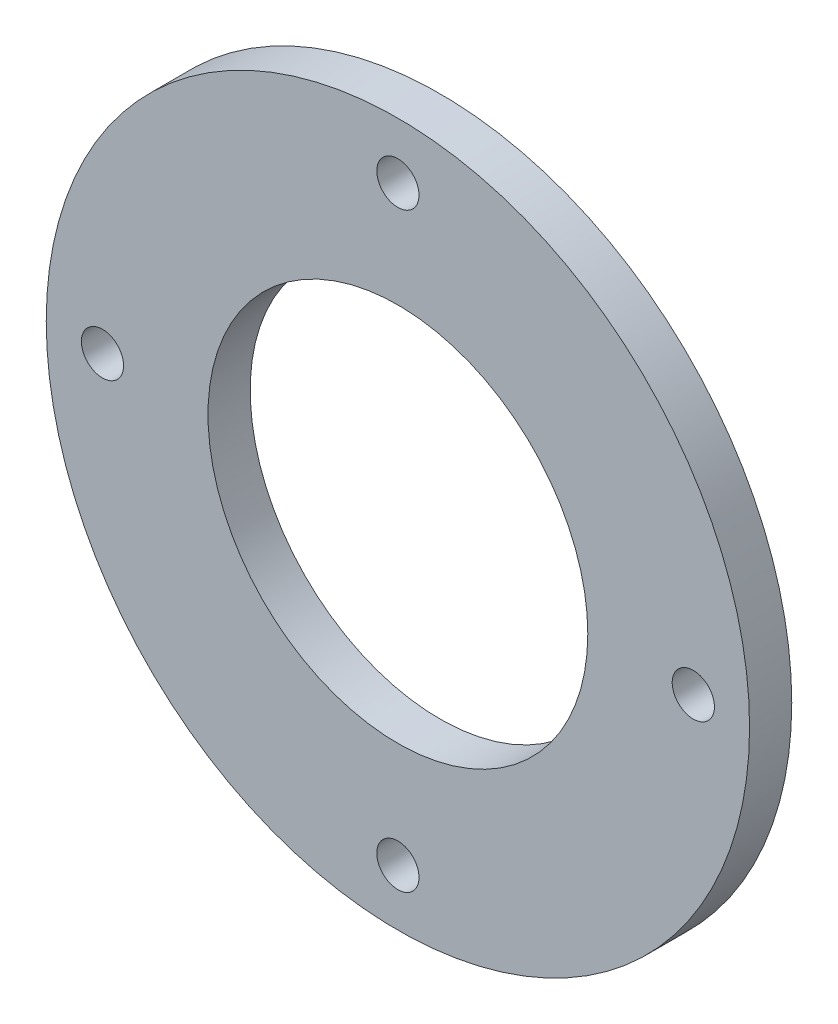
SolidWorks part; units mm, degrees
ref_plane "Front Plane" through (0, 0, 0) normal (0, 0, 1) x (1, 0, 0)
ref_plane "Top Plane" through (0, 0, 0) normal (0, 1, 0) x (1, 0, 0)
ref_plane "Right Plane" through (0, 0, 0) normal (1, 0, 0) x (0, 0, -1)
sketch "Sketch1" plane through (0, 0, 0) normal (0, 0, 1) x (1, 0, 0)
  circle A0 centre (0, 0) radius 25
  circle A1 centre (0, 0) radius 13.5
  circle A2 centre (0, 21) radius 1.5
  circle A3 centre (21, 0) radius 1.5
  circle A4 centre (0, -21) radius 1.5
  circle A5 centre (-21, 0) radius 1.5
  point P15 (0, 0)
  dimension "D1" = 50
  dimension "D2" = 21
  dimension "D4" = 27
  dimension "D3" = 4
extrude "Boss-Extrude1" add sketch "Sketch1" along normal blind 3
